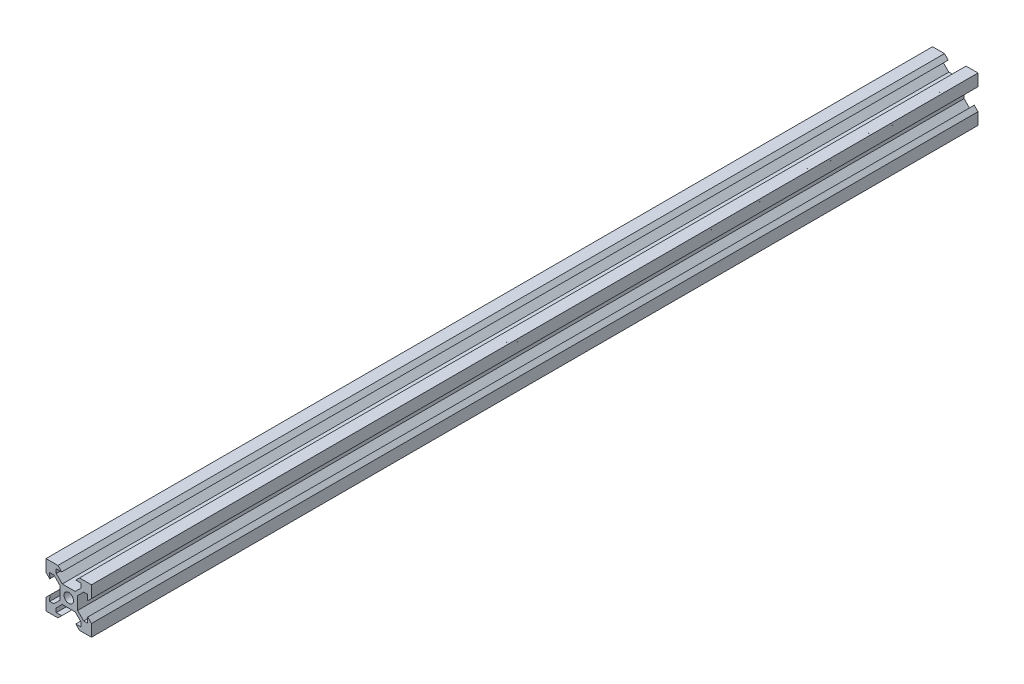
SolidWorks part; units mm, degrees
material "6061-T6 (SS)"
ref_plane "Front Plane" through (0, 0, 0) normal (0, 0, 1) x (1, 0, 0)
ref_plane "Top Plane" through (0, 0, 0) normal (0, 1, 0) x (1, 0, 0)
ref_plane "Right Plane" through (0, 0, 0) normal (1, 0, 0) x (0, 0, -1)
sketch "Sketch1" plane through (0, 0, 0) normal (0, 0, 1) x (1, 0, 0)
  line L0 (2.8343, 3.894) -> (5.5, 6.5588)
  line L1 (2.8343, -3.894) -> (-2.8343, -3.894)
  line L2 (3.8948, -2.8332) -> (3.8948, 2.8332)
  line L3 (2.8343, 3.894) -> (-2.8343, 3.894)
  line L4 (-3.8948, -2.8332) -> (-3.8948, 2.8332)
  line L5 (3.8994, -3.9006) -> (-3.8994, 3.9006) construction
  line L6 (3.9006, 3.8994) -> (-3.9006, -3.8994) construction
  line L7 (10, 4.747) -> (10, 9.9986)
  line L8 (5.5, 6.5588) -> (5.5, 8.3491)
  line L9 (5.5, 8.3491) -> (3.1, 8.3491)
  line L10 (3.1, 8.3491) -> (4.75, 9.9986)
  line L11 (4.75, 9.9986) -> (10, 9.9986)
  line L12 (8.35, 3.0975) -> (10, 4.747)
  line L13 (8.3507, 5.4975) -> (8.35, 3.0975)
  line L14 (6.5605, 5.498) -> (8.3507, 5.4975)
  line L15 (3.8948, 2.8332) -> (6.5605, 5.498)
  line L16 (0, -55) -> (0, 55) construction
  line L17 (-3.8948, 2.8332) -> (-6.5605, 5.498)
  line L18 (-6.5605, 5.498) -> (-8.3507, 5.4975)
  line L19 (-8.3507, 5.4975) -> (-8.35, 3.0975)
  line L20 (-8.35, 3.0975) -> (-10, 4.747)
  line L21 (-4.75, 9.9986) -> (-10, 9.9986)
  line L22 (-3.1, 8.3491) -> (-4.75, 9.9986)
  line L23 (-5.5, 8.3491) -> (-3.1, 8.3491)
  line L24 (-5.5, 6.5588) -> (-5.5, 8.3491)
  line L25 (-10, 4.747) -> (-10, 9.9986)
  line L26 (-2.8343, 3.894) -> (-5.5, 6.5588)
  line L27 (55, 0) -> (-55, 0) construction
  line L28 (3.8948, -2.8332) -> (6.5605, -5.498)
  line L29 (2.8343, -3.894) -> (5.5, -6.5588)
  line L30 (-3.8948, -2.8332) -> (-6.5605, -5.498)
  line L31 (-2.8343, -3.894) -> (-5.5, -6.5588)
  line L32 (-8.3507, -5.4975) -> (-8.35, -3.0975)
  line L33 (-8.35, -3.0975) -> (-10, -4.747)
  line L34 (8.3507, -5.4975) -> (8.35, -3.0975)
  line L35 (8.35, -3.0975) -> (10, -4.747)
  line L36 (-10, -4.747) -> (-10, -9.9986)
  line L37 (-5.5, -6.5588) -> (-5.5, -8.3491)
  line L38 (-5.5, -8.3491) -> (-3.1, -8.3491)
  line L39 (-3.1, -8.3491) -> (-4.75, -9.9986)
  line L40 (-4.75, -9.9986) -> (-10, -9.9986)
  line L41 (-6.5605, -5.498) -> (-8.3507, -5.4975)
  line L42 (6.5605, -5.498) -> (8.3507, -5.4975)
  line L43 (4.75, -9.9986) -> (10, -9.9986)
  line L44 (3.1, -8.3491) -> (4.75, -9.9986)
  line L45 (5.5, -8.3491) -> (3.1, -8.3491)
  line L46 (5.5, -6.5588) -> (5.5, -8.3491)
  line L47 (10, -4.747) -> (10, -9.9986)
  circle A0 centre (0, 0) radius 2.1
  point P0 (0, 0)
  dimension "D6" = 4.2
  dimension "D1" = 7.8
  dimension "D2" = 20
  dimension "D3" = 11
  dimension "D4" = 9.5
  dimension "D5" = 6.2
  dimension "D7" = 1.5
extrude "Boss-Extrude1" add sketch "Sketch1" along normal blind 390
